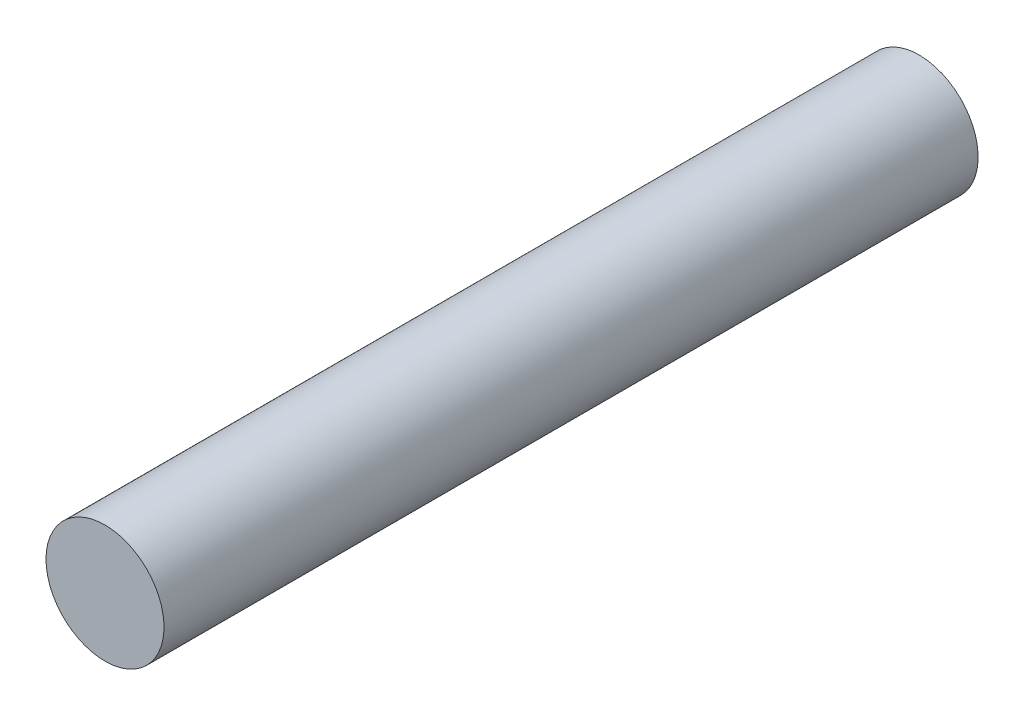
SolidWorks part; units mm, degrees
ref_plane "Plan de face" through (0, 0, 0) normal (0, 0, 1) x (1, 0, 0)
ref_plane "Plan de dessus" through (0, 0, 0) normal (0, 1, 0) x (1, 0, 0)
ref_plane "Plan de droite" through (0, 0, 0) normal (1, 0, 0) x (0, 0, -1)
sketch "Esquisse1" plane through (0, 0, 0) normal (0, 0, 1) x (1, 0, 0)
  circle A0 centre (0, 0) radius 4
  dimension "D1" = 8
extrude "Boss.-Extru.1" add sketch "Esquisse1" along normal blind 55.2
